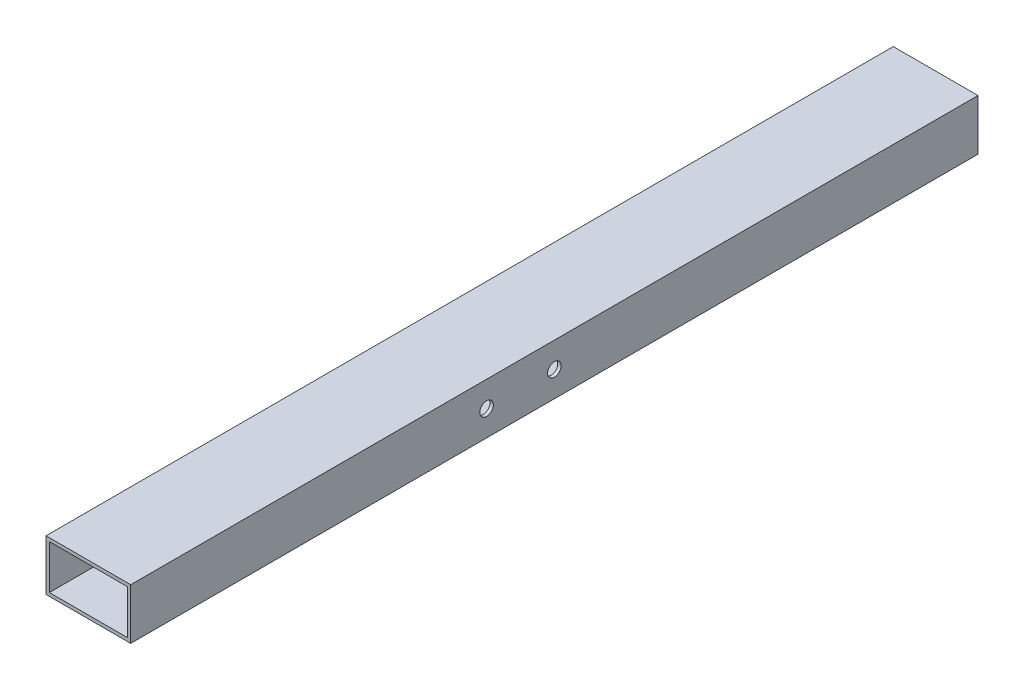
SolidWorks part; units mm, degrees
material "1023 Carbon Steel Sheet (SS)"
ref_plane "Front Plane" through (0, 0, 0) normal (0, 0, 1) x (1, 0, 0)
ref_plane "Top Plane" through (0, 0, 0) normal (0, 1, 0) x (1, 0, 0)
ref_plane "Right Plane" through (0, 0, 0) normal (1, 0, 0) x (0, 0, -1)
sketch "Sketch1" plane through (0, 0, 0) normal (0, 0, 1) x (1, 0, 0)
  line L0 (2, -2) -> (48, -2)
  line L1 (0, 0) -> (50, 0)
  line L2 (0, 0) -> (0, -30)
  line L3 (0, -30) -> (50, -30)
  line L4 (50, 0) -> (50, -30)
  line L5 (48, -2) -> (48, -28)
  line L6 (2, -28) -> (48, -28)
  line L7 (2, -2) -> (2, -28)
  dimension "D1" = 50
  dimension "D2" = 30
  dimension "D3" = 2
extrude "Boss-Extrude1" add sketch "Sketch1" along normal blind 500
sketch "Sketch2" plane through (50, 0, 0) normal (1, 0, 0) x (0, 0, -1)
  line L1 (-500, -30) -> (-500, 0) construction
  line L3 (-500, 0) -> (0, 0) construction
  circle A1 centre (-250, -15) radius 4
  circle A2 centre (-290, -15) radius 4
  dimension "D1" = 250
  dimension "D2" = 8
  dimension "D3" = 15
  dimension "D4" = 8
  dimension "D5" = 40
  dimension "D6" = 15
extrude "Cut-Extrude1" cut sketch "Sketch2" against normal through all
